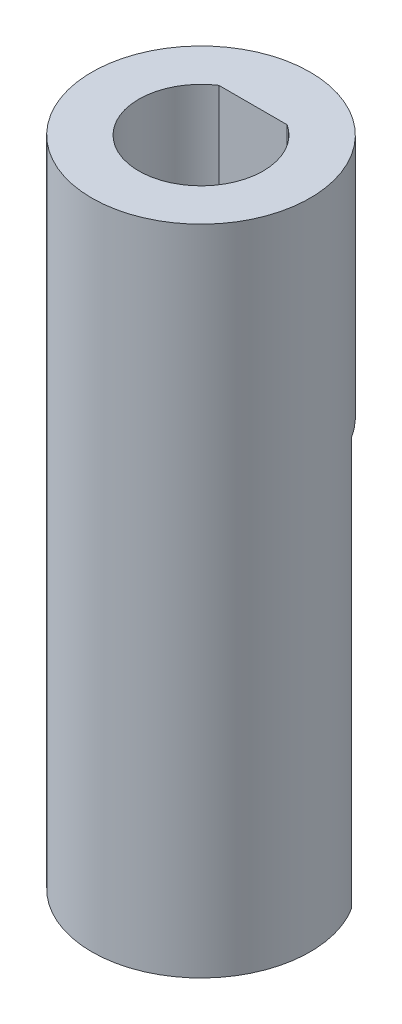
SolidWorks part; units mm, degrees
ref_plane "Ön Düzlem" through (0, 0, 0) normal (0, 0, 1) x (1, 0, 0)
ref_plane "Üst Düzlem" through (0, 0, 0) normal (0, 1, 0) x (1, 0, 0)
ref_plane "Sağ Düzlem" through (0, 0, 0) normal (1, 0, 0) x (0, 0, -1)
sketch "Çizim1" plane through (0, 0, 0) normal (0, 1, 0) x (1, 0, 0)
  line L1 (-4.5277, 2.85) -> (4.5277, 2.85)
  arc A0 (-4.5277, 2.85) -> (4.5277, 2.85) centre (0, 0) ccw
  circle A1 centre (0, 0) radius 2.2
  dimension "D1" = 10.7
  dimension "D2" = 4.4
extrude "Yükseklik-Ekstrüzyon1" add sketch "Çizim1" along normal blind 20
ref_plane "Düzlem1" through (0, 20, 0) normal (0, 1, 0) x (1, 0, 0)
sketch "Çizim2" plane through (0, 20, 0) normal (0, 1, 0) x (1, 0, 0)
  circle A0 centre (0, 0) radius 5.35
  circle A1 centre (0, 0) radius 2.2
  dimension "D1" = 4.4
  dimension "D2" = 10.7
extrude "Yükseklik-Ekstrüzyon2" add sketch "Çizim2" along normal blind 12
ref_plane "Düzlem2" through (0, 32, 0) normal (0, 1, 0) x (1, 0, 0)
sketch "Çizim3" plane through (0, 32, 0) normal (0, 1, 0) x (1, 0, 0)
  line L2 (-1.6733, 2.55) -> (1.6733, 2.55)
  arc A0 (-1.6733, 2.55) -> (1.6733, 2.55) centre (0, 0) ccw
extrude "Kes-Ekstrüzyon1" cut sketch "Çizim3" against normal blind 10
